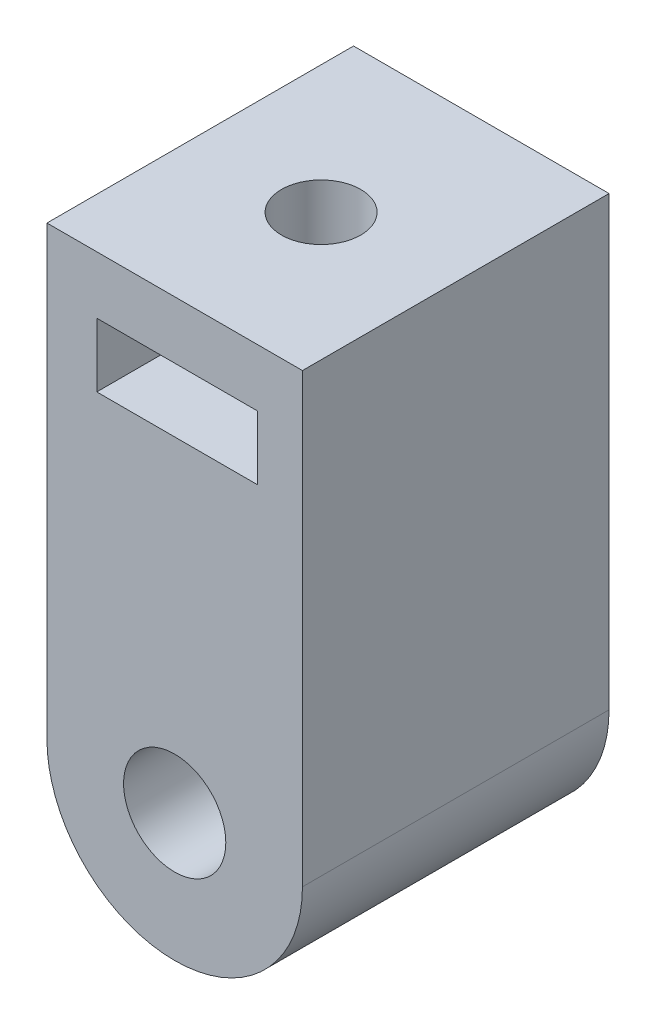
SolidWorks part; units mm, degrees
ref_plane "Спереди" through (0, 0, 0) normal (0, 0, 1) x (1, 0, 0)
ref_plane "Сверху" through (0, 0, 0) normal (0, 1, 0) x (1, 0, 0)
ref_plane "Справа" through (0, 0, 0) normal (1, 0, 0) x (0, 0, -1)
sketch "Эскиз1" plane through (0, 0, 0) normal (0, 0, 1) x (1, 0, 0)
  circle A0 centre (0, 0) radius 2
  circle A1 centre (0, 0) radius 5
extrude "Бобышка-Вытянуть1" add sketch "Эскиз1" along normal blind 12
sketch "Эскиз2" plane through (0, 0, 12) normal (0, 0, 1) x (1, 0, 0)
  line L0 (-5, 0) -> (5, 0)
  line L2 (-5, 0) -> (-5, 17.5)
  line L3 (-5, 17.5) -> (5, 17.5)
  line L4 (5, 0) -> (5, 17.5)
  line L5 (0, 0) -> (5, 17.5) construction
  line L6 (-5, 17.5) -> (0, 0) construction
  point P0 (0, 0)
  point P9 (0, 0)
extrude "Бобышка-Вытянуть2" add sketch "Эскиз2" against normal up to surface (12 mm away) up to face at (5, 0, 0)
sketch "Эскиз3" plane through (0, 0, 12) normal (0, 0, 1) x (1, 0, 0)
  line L0 (-2, 0) -> (2, 0) construction
  circle A0 centre (0, 0) radius 2
extrude "Вырез-Вытянуть1" cut sketch "Эскиз3" against normal through all
sketch "Эскиз5" plane through (0, 0, 12) normal (0, 0, 1) x (1, 0, 0)
  line L1 (3.25, 15.25) -> (-3.05, 15.25)
  line L2 (3.25, 15.25) -> (3.25, 12.75)
  line L3 (3.25, 12.75) -> (-3.05, 12.75)
  line L4 (-3.05, 15.25) -> (-3.05, 12.75)
  line L5 (3.25, 15.25) -> (-3.05, 12.75) construction
  line L6 (3.25, 12.75) -> (-3.05, 15.25) construction
  point P0 (0.1, 14)
extrude "Вырез-Вытянуть3" cut sketch "Эскиз5" against normal blind 8.48
sketch "Эскиз8" plane through (0, 12.75, 0) normal (0, 1, 0) x (1, 0, 0)
  line L0 (-3.05, -12) -> (-5.0865, -12)
sketch "Эскиз10" plane through (-5, 0, 0) normal (-1, 0, 0) x (0, 0, 1)
  line L0 (11.0983, 3.2685) -> (12, 3.2685) construction
  line L1 (1.4417, 2.925) -> (11.0983, 2.925)
  line L2 (1.4417, 2.925) -> (1.4417, 10.475)
  line L3 (1.4417, 10.475) -> (11.0983, 10.475)
  line L4 (11.0983, 2.925) -> (11.0983, 10.475)
  line L5 (1.4417, 2.925) -> (11.0983, 10.475) construction
  line L6 (1.4417, 10.475) -> (11.0983, 2.925) construction
  line L7 (12, 17.5) -> (12, 0) construction
  line L8 (6.27, 6.7) -> (11.0983, 6.7) construction
  line L9 (6.27, 2.925) -> (12, 2.925) construction
  point P0 (6.27, 6.7)
  point P10 (0, 0)
extrude "Вырез-Вытянуть5" cut sketch "Эскиз10" against normal blind 9.4
sketch "Эскиз6" plane through (0, 17.5, 0) normal (0, 1, 0) x (1, 0, 0)
  line L0 (0, -12) -> (0, -6.27) construction
  line L1 (5, -12) -> (-5, -12) construction
  circle A0 centre (0, -6.27) radius 1.55
extrude "Вырез-Вытянуть4" cut sketch "Эскиз6" against normal up to surface (7.025 mm away) up to face at (-0.3, 10.475, 6.27)
sketch "Эскиз11" plane through (0, 12.75, 0) normal (0, 1, 0) x (1, 0, 0)
  line L0 (-3, -6.27) -> (3, -6.27) construction
  line L1 (3, -6.27) -> (1.5, -3.6719)
  line L2 (1.5, -3.6719) -> (-1.5, -3.6719)
  line L3 (-1.5, -3.6719) -> (-3, -6.27)
  line L4 (-3, -6.27) -> (-1.5, -8.8681)
  line L5 (-1.5, -8.8681) -> (1.5, -8.8681)
  line L6 (1.5, -8.8681) -> (3, -6.27)
  line L7 (-1.5, -3.6719) -> (-1.5, -3.52) construction
  line L8 (-3.05, -3.52) -> (3.25, -3.52) construction
  circle A0 centre (0, -6.27) radius 3 construction
